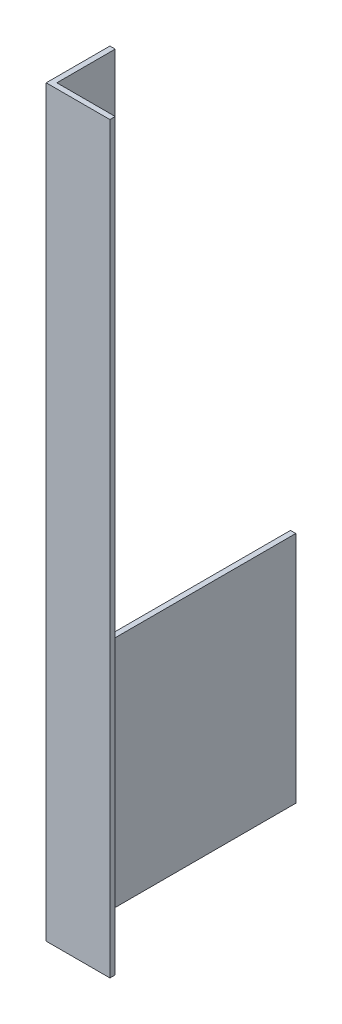
SolidWorks part; units mm, degrees
material "Galvanized Steel"
ref_plane "Front Plane" through (0, 0, 0) normal (0, 0, 1) x (1, 0, 0)
ref_plane "Top Plane" through (0, 0, 0) normal (0, 1, 0) x (1, 0, 0)
ref_plane "Right Plane" through (0, 0, 0) normal (1, 0, 0) x (0, 0, -1)
sketch "Sketch18" plane through (0, 0, 0) normal (0, 1, 0) x (1, 0, 0)
  line L0 (3.175, 38.1) -> (3.175, 3.175)
  line L1 (0, 0) -> (38.1, 0)
  line L2 (0, 0) -> (0, 38.1)
  line L3 (0, 38.1) -> (3.175, 38.1)
  line L4 (38.1, 0) -> (38.1, 3.175)
  line L5 (3.175, 3.175) -> (38.1, 3.175)
  dimension "D1" = 38.1
  dimension "D2" = 3.175
  dimension "D3" = 90
extrude "Boss-Extrude1" add sketch "Sketch18" along normal mid plane 444.5
sketch "Sketch19" plane through (0, 0, 0) normal (1, 0, 0) x (0, 0, -1)
  line L1 (38.1, -222.25) -> (146.05, -222.25)
  line L2 (38.1, -222.25) -> (38.1, -82.55)
  line L3 (38.1, -82.55) -> (146.05, -82.55)
  line L4 (146.05, -222.25) -> (146.05, -82.55)
  dimension "D1" = 107.95
  dimension "D2" = 139.7
extrude "Boss-Extrude2" add sketch "Sketch19" along normal blind 3.175
